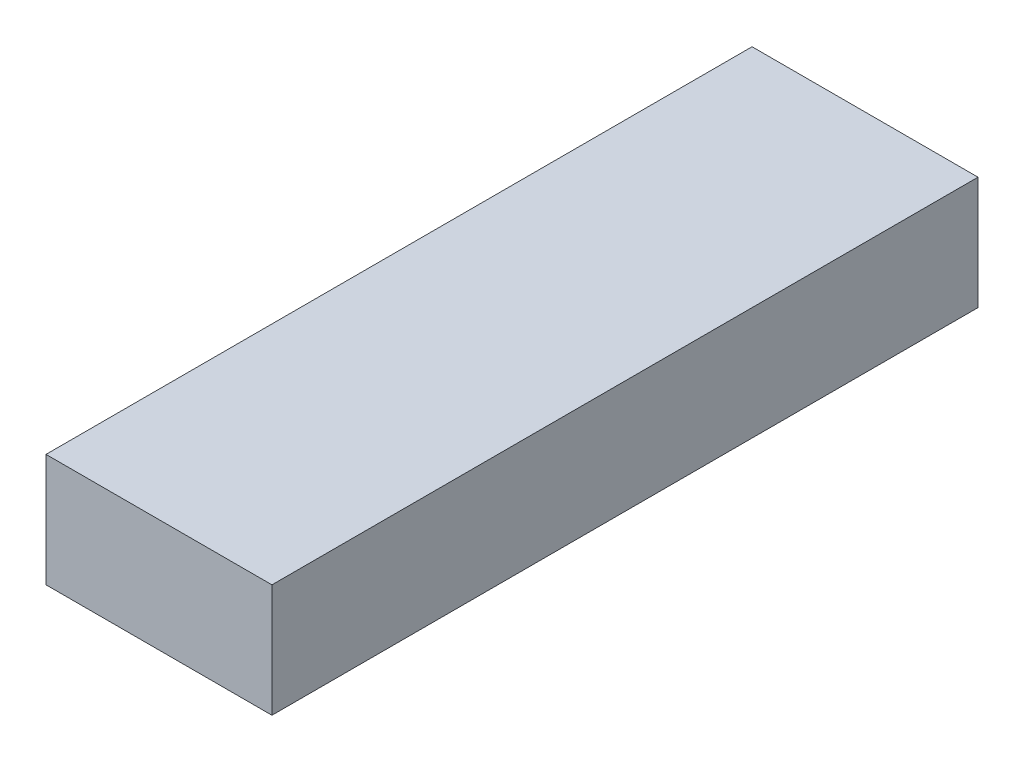
SolidWorks part; units mm, degrees
material "Pine"
ref_plane "X-Y Datum" through (0, 0, 0) normal (0, 0, 1) x (1, 0, 0)
ref_plane "X-Z Datum" through (0, 0, 0) normal (0, 1, 0) x (1, 0, 0)
ref_plane "Y-Z Datum" through (0, 0, 0) normal (1, 0, 0) x (0, 0, -1)
sketch "Sketch1" plane through (0, 0, 0) normal (0, 0, 1) x (1, 0, 0)
  line L1 (-50.8, 25.4) -> (50.8, 25.4)
  line L2 (-50.8, 25.4) -> (-50.8, -25.4)
  line L3 (-50.8, -25.4) -> (50.8, -25.4)
  line L4 (50.8, 25.4) -> (50.8, -25.4)
  line L5 (-50.8, 25.4) -> (50.8, -25.4) construction
  line L6 (-50.8, -25.4) -> (50.8, 25.4) construction
  point P0 (0, 0)
  dimension "D1" = 101.6
  dimension "D2" = 50.8
extrude "Boss-Extrude1" add sketch "Sketch1" along normal blind 317.5
